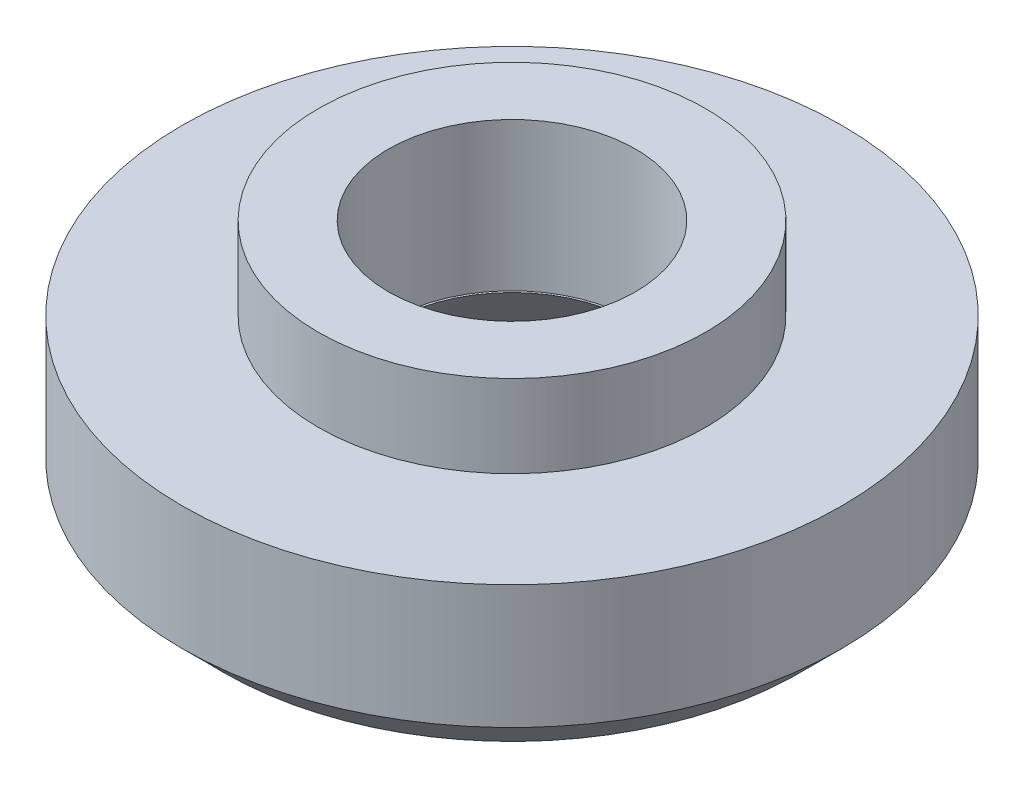
SolidWorks part; units mm, degrees
material "1023 Carbon Steel Sheet (SS)"
ref_plane "Front Plane" through (0, 0, 0) normal (0, 0, 1) x (1, 0, 0)
ref_plane "Top Plane" through (0, 0, 0) normal (0, 1, 0) x (1, 0, 0)
ref_plane "Right Plane" through (0, 0, 0) normal (1, 0, 0) x (0, 0, -1)
sketch "Sketch2" plane through (0, 0, 0) normal (0, 1, 0) x (1, 0, 0)
  circle A0 centre (0, 0) radius 2.35
  dimension "D1" = 4.7
extrude "Boss-Extrude1" add sketch "Sketch2" along normal blind 1
sketch "Sketch3" plane through (0, 0, 0) normal (0, -1, 0) x (1, 0, 0)
  circle A0 centre (0, 0) radius 4
  dimension "D1" = 8
extrude "Boss-Extrude2" add sketch "Sketch3" along normal blind 2
sketch "Sketch4" plane through (0, -2, 0) normal (0, -1, 0) x (1, 0, 0)
  circle A0 centre (0, 0) radius 2.675
  dimension "D1" = 5.35
extrude "Cut-Extrude1" cut sketch "Sketch4" against normal blind 1.8 draft 45
sketch "Sketch5" plane through (0, 1, 0) normal (0, 1, 0) x (1, 0, 0)
  circle A0 centre (0, 0) radius 1.5
  dimension "D1" = 3
extrude "Cut-Extrude2" cut sketch "Sketch5" against normal blind 1.8
chamfer "Chamfer1" distance 0.5 angle 45 1 edges at (0, -2, -4)
